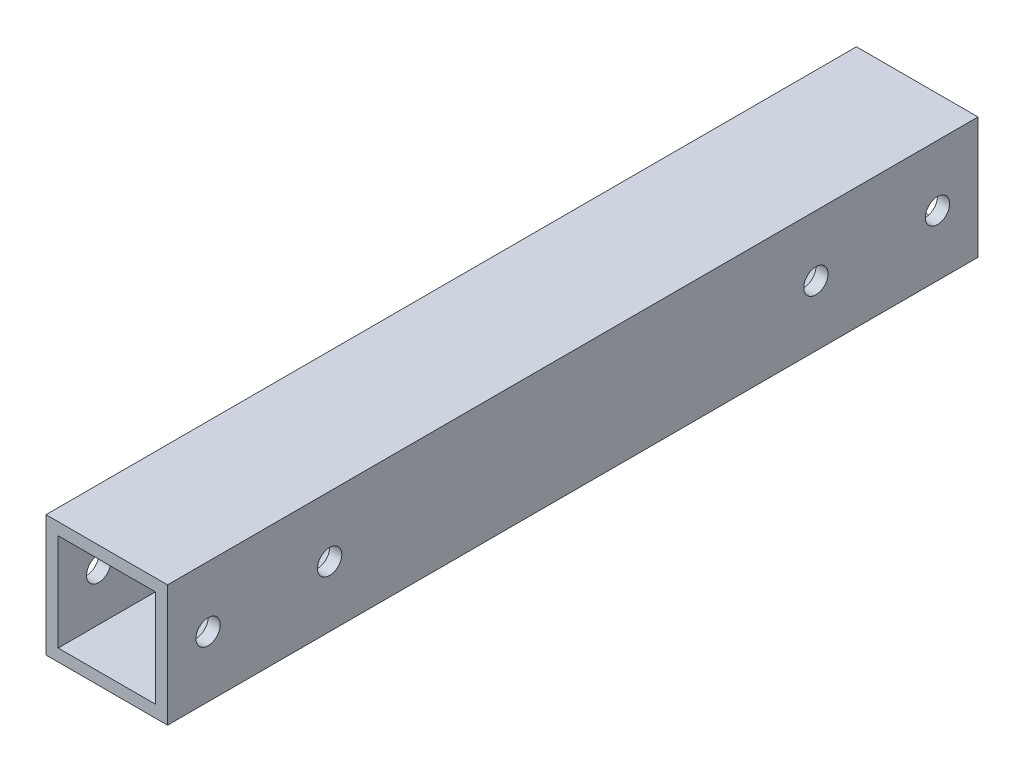
SolidWorks part; units mm, degrees
ref_plane "Plan de face" through (0, 0, 0) normal (0, 0, 1) x (1, 0, 0)
ref_plane "Plan de dessus" through (0, 0, 0) normal (0, 1, 0) x (1, 0, 0)
ref_plane "Plan de droite" through (0, 0, 0) normal (1, 0, 0) x (0, 0, -1)
sketch "Esquisse1" plane through (0, 0, 0) normal (0, 0, 1) x (1, 0, 0)
  line L1 (-7.5, -7.5) -> (7.5, -7.5)
  line L2 (-7.5, -7.5) -> (-7.5, 7.5)
  line L3 (-7.5, 7.5) -> (7.5, 7.5)
  line L4 (7.5, -7.5) -> (7.5, 7.5)
  line L5 (-7.5, -7.5) -> (7.5, 7.5) construction
  line L6 (-7.5, 7.5) -> (7.5, -7.5) construction
  point P0 (0, 0)
  dimension "D1" = 15
  dimension "D2" = 15
extrude "Extrusion1" add sketch "Esquisse1" along normal blind 100
sketch "Esquisse2" plane through (0, 0, 100) normal (0, 0, 1) x (1, 0, 0)
  line L0 (7.5, 7.5) -> (-7.5, 7.5) construction
  line L1 (-6, -6) -> (6, -6)
  line L2 (-6, -6) -> (-6, 6)
  line L3 (-6, 6) -> (6, 6)
  line L4 (6, -6) -> (6, 6)
  line L5 (-6, -6) -> (6, 6) construction
  line L6 (-6, 6) -> (6, -6) construction
  line L7 (7.5, -7.5) -> (7.5, 7.5) construction
  point P0 (0, 0)
  dimension "D1" = 1.5
  dimension "D2" = 1.5
extrude "Extrusion2" cut sketch "Esquisse2" against normal through all
sketch "Esquisse3" plane through (7.5, 0, 0) normal (1, 0, 0) x (0, 0, -1)
  circle A0 centre (-5, 0) radius 1.5
  dimension "D1" = 3
extrude "Enlèv. mat.-Extru.1" cut sketch "Esquisse3" against normal through all
sketch "Esquisse4" plane through (7.5, 0, 0) normal (1, 0, 0) x (0, 0, -1)
  circle A0 centre (-20, 0) radius 1.5
  dimension "D1" = 3
extrude "Enlèv. mat.-Extru.2" cut sketch "Esquisse4" against normal through all
sketch "Esquisse5" plane through (7.5, 0, 0) normal (1, 0, 0) x (0, 0, -1)
  circle A0 centre (-95, 0) radius 1.5
  circle A1 centre (-80, 0) radius 1.5
extrude "Enlèv. mat.-Extru.3" cut sketch "Esquisse5" against normal through all
